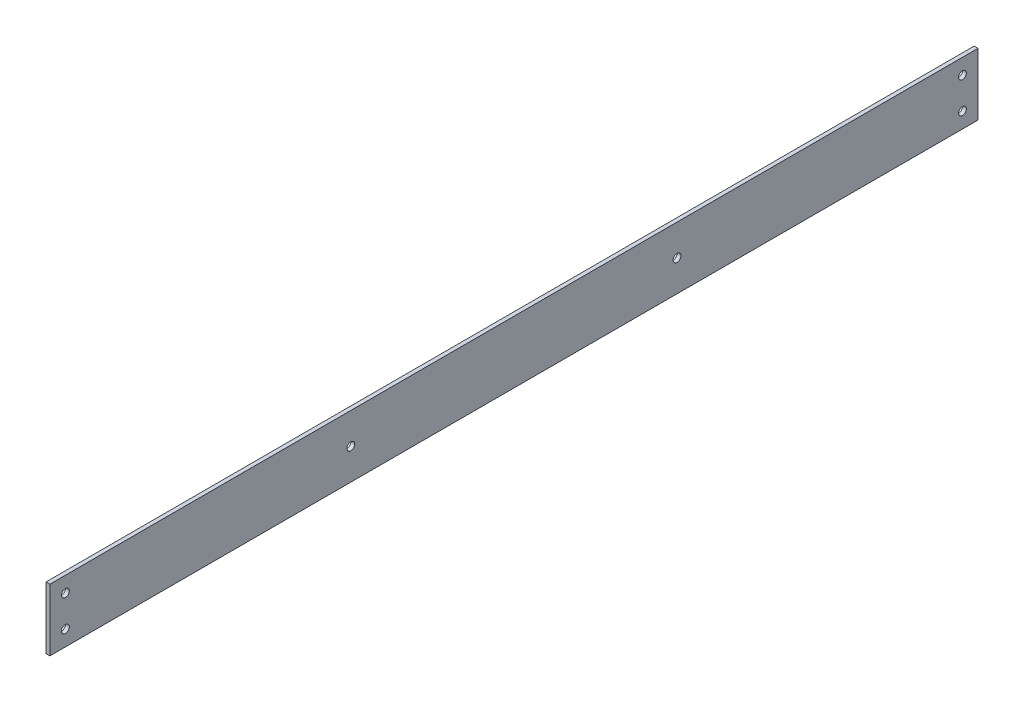
SolidWorks part; units mm, degrees
material "1060 Alloy"
ref_plane "Front Plane" through (0, 0, 0) normal (0, 0, 1) x (1, 0, 0)
ref_plane "Top Plane" through (0, 0, 0) normal (0, 1, 0) x (1, 0, 0)
ref_plane "Right Plane" through (0, 0, 0) normal (1, 0, 0) x (0, 0, -1)
sketch "Sketch1" plane through (0, 0, 0) normal (0, 0, 1) x (1, 0, 0)
  line L1 (-1.5875, -25.4) -> (1.5875, -25.4)
  line L2 (-1.5875, -25.4) -> (-1.5875, 25.4)
  line L3 (-1.5875, 25.4) -> (1.5875, 25.4)
  line L4 (1.5875, -25.4) -> (1.5875, 25.4)
  line L5 (-1.5875, -25.4) -> (1.5875, 25.4) construction
  line L6 (-1.5875, 25.4) -> (1.5875, -25.4) construction
  point P0 (0, 0)
  dimension "D1" = 50.8
  dimension "D2" = 3.175
extrude "Boss-Extrude1" add sketch "Sketch1" along normal blind 809.625
sketch "Sketch2" plane through (1.5875, 0, 0) normal (1, 0, 0) x (0, 0, -1)
  line L0 (0, -25.4) -> (0, 25.4) construction
  line L1 (-809.625, 25.4) -> (0, 25.4) construction
  line L3 (-809.625, -25.4) -> (0, -25.4) construction
  line L4 (-404.8125, -25.4) -> (-404.8125, 25.4) construction
  line L5 (-809.625, -25.4) -> (0, -25.4) construction
  circle A0 centre (-38.1, 12.7) radius 3.175
  circle A1 centre (-38.1, -12.7) radius 3.175
  circle A2 centre (-771.525, 12.7) radius 3.175
  circle A3 centre (-771.525, -12.7) radius 3.175
  dimension "D3" = 6.35
  dimension "D6" = 6.35
  dimension "D1" = 38.1
  dimension "D2" = 12.7
  dimension "D4" = 38.1
  dimension "D5" = 12.7
extrude "Cut-Extrude1" cut sketch "Sketch2" against normal through all
sketch "Sketch3" plane through (-1.5875, 0, 0) normal (-1, 0, 0) x (0, 0, 1)
  line L0 (809.625, 25.4) -> (0, 25.4) construction
  line L1 (809.625, -25.4) -> (784.225, -25.4)
  line L2 (809.625, -25.4) -> (809.625, 25.4)
  line L3 (809.625, 25.4) -> (784.225, 25.4)
  line L4 (784.225, -25.4) -> (784.225, 25.4)
  line L5 (809.625, -25.4) -> (0, -25.4) construction
  line L6 (0, -25.4) -> (25.4, -25.4)
  line L7 (0, -25.4) -> (0, 25.4)
  line L8 (0, 25.4) -> (25.4, 25.4)
  line L9 (25.4, -25.4) -> (25.4, 25.4)
  line L10 (0, 25.4) -> (0, -25.4) construction
  dimension "D1" = 25.4
extrude "Cut-Extrude2" cut sketch "Sketch3" against normal through all
sketch "Sketch4" plane through (-1.5875, 0, 0) normal (-1, 0, 0) x (0, 0, 1)
  line L0 (784.225, -25.4) -> (25.4, -25.4) construction
  line L2 (784.225, 25.4) -> (784.225, -25.4) construction
  circle A2 centre (271.4625, 0) radius 3.175
  circle A3 centre (538.1625, 0) radius 3.175
  point P10 (0, 0)
  point P11 (285.6018, 0)
  point P12 (0, 0)
  point P15 (0, 0)
  point P16 (0, 0)
  point P17 (0, 0)
  point P18 (25.4, 36.1565)
  point P19 (0, 0)
  point P21 (0, 0)
  point P22 (0, 0)
  point P23 (71.7285, -4.137)
  point P24 (0, 0)
  dimension "D1" = 6.35
  dimension "D2" = 25.4
  dimension "D3" = 266.7
  dimension "D4" = 246.0625
extrude "Cut-Extrude3" cut sketch "Sketch4" against normal through all
